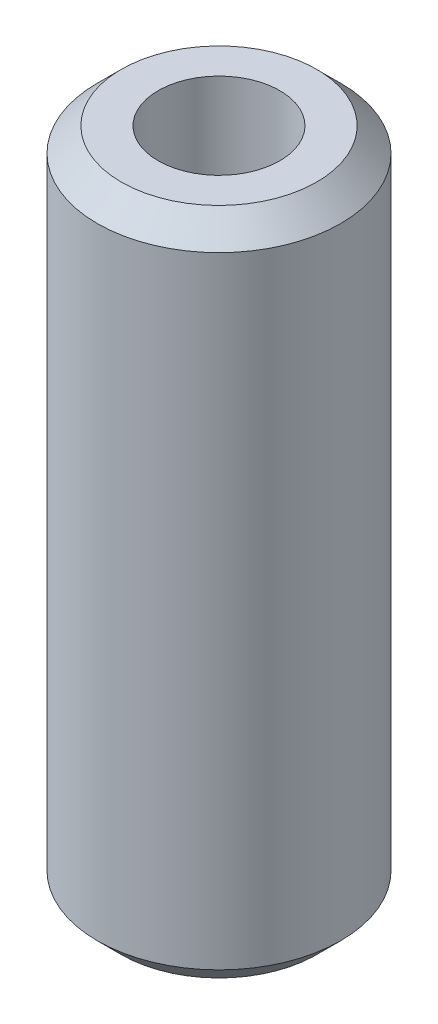
SolidWorks part; units mm, degrees
ref_plane "Front Plane" through (0, 0, 0) normal (0, 0, 1) x (1, 0, 0)
ref_plane "Top Plane" through (0, 0, 0) normal (0, 1, 0) x (1, 0, 0)
ref_plane "Right Plane" through (0, 0, 0) normal (1, 0, 0) x (0, 0, -1)
sketch "Sketch1" plane through (0, 0, 0) normal (0, 1, 0) x (1, 0, 0)
  circle A0 centre (0, 0) radius 6.35
  circle A1 centre (0, 0) radius 12.7
  dimension "D1" = 12.7
  dimension "D2" = 25.4
extrude "Boss-Extrude1" add sketch "Sketch1" along normal mid plane 69.85
chamfer "Chamfer2" distance 2.5 angle 45 2 edges at (0, -34.925, 12.7) (0, 34.925, 12.7)
